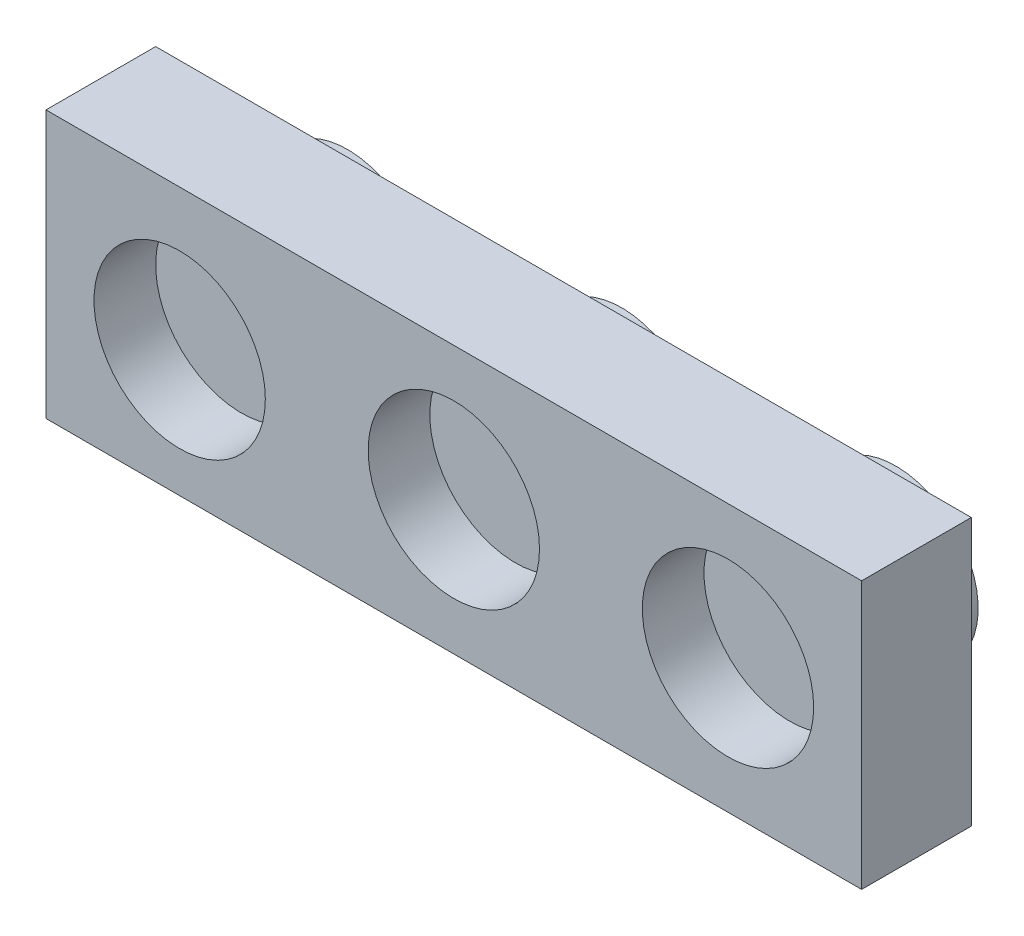
SolidWorks part; units mm, degrees
ref_plane "Спереди" through (0, 0, 0) normal (0, 0, 1) x (1, 0, 0)
ref_plane "Сверху" through (0, 0, 0) normal (0, 1, 0) x (1, 0, 0)
ref_plane "Справа" through (0, 0, 0) normal (1, 0, 0) x (0, 0, -1)
sketch "Эскиз1" plane through (0, 0, 0) normal (0, 0, 1) x (1, 0, 0)
  line L1 (-11.9, -3.9) -> (11.9, -3.9)
  line L2 (-11.9, -3.9) -> (-11.9, 3.9)
  line L3 (-11.9, 3.9) -> (11.9, 3.9)
  line L4 (11.9, -3.9) -> (11.9, 3.9)
  line L5 (-11.9, -3.9) -> (11.9, 3.9) construction
  line L6 (-11.9, 3.9) -> (11.9, -3.9) construction
  point P0 (0, 0)
  dimension "D1" = 23.8
  dimension "D2" = 7.8
extrude "Бобышка-Вытянуть1" add sketch "Эскиз1" along normal blind 3.2
sketch "Эскиз2" plane through (0, 0, 0) normal (0, 0, -1) x (-1, 0, 0)
  circle A0 centre (0, 0) radius 2.4
  circle A1 centre (8, 0) radius 2.4
  circle A2 centre (-8, 0) radius 2.4
  dimension "D1" = 8
  dimension "D2" = 8
extrude "Бобышка-Вытянуть2" add sketch "Эскиз2" along normal blind 1.7
sketch "Эскиз3" plane through (0, 0, 3.2) normal (0, 0, 1) x (1, 0, 0)
  circle A0 centre (0, 0) radius 2.5
  circle A1 centre (-8, -0.2111) radius 2.5
  circle A2 centre (8, 0) radius 2.5
  point P7 (0, 0)
  point P8 (0, 0)
  dimension "D1" = 8
  dimension "D2" = 8
extrude "Вырез-Вытянуть1" cut sketch "Эскиз3" against normal blind 1.8
